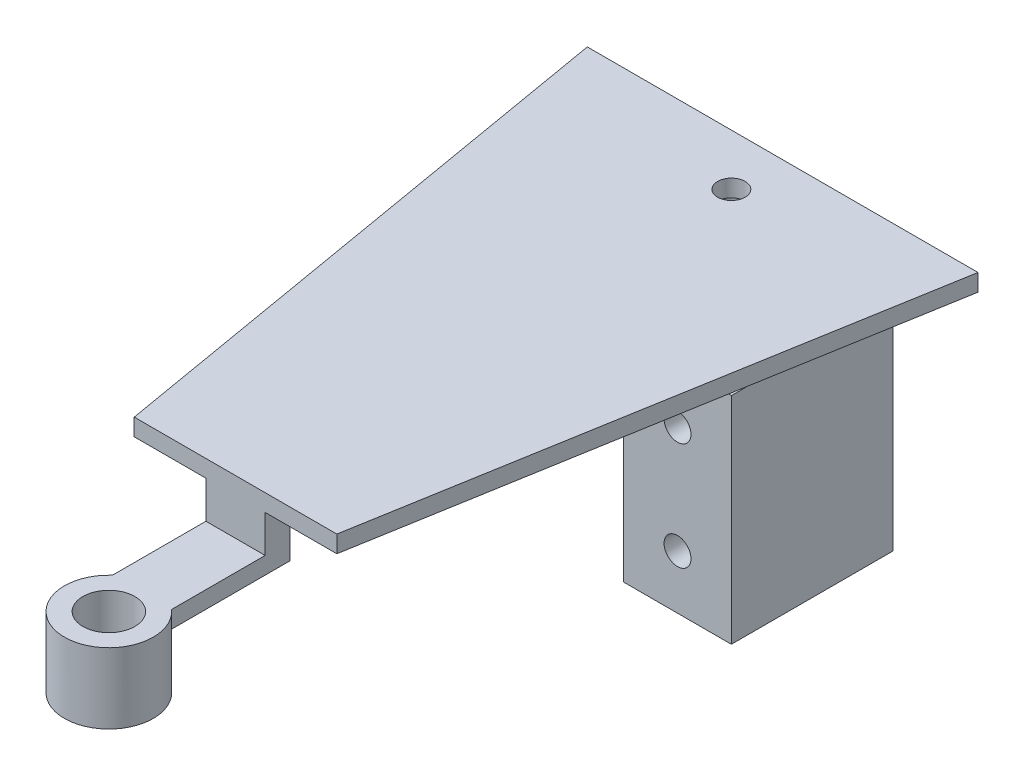
SolidWorks part; units mm, degrees
ref_plane "Front Plane" through (0, 0, 0) normal (0, 0, 1) x (1, 0, 0)
ref_plane "Top Plane" through (0, 0, 0) normal (0, 1, 0) x (1, 0, 0)
ref_plane "Right Plane" through (0, 0, 0) normal (1, 0, 0) x (0, 0, -1)
sketch "Sketch1" plane through (0, 0, 0) normal (0, 0, 1) x (1, 0, 0)
  line L0 (10, 40) -> (10, 0) construction
  line L1 (0, 0) -> (20, 0)
  line L2 (0, 0) -> (0, 40)
  line L3 (0, 40) -> (20, 40)
  line L4 (20, 0) -> (20, 40)
  circle A0 centre (10, 30) radius 2.5
  circle A1 centre (10, 10) radius 2.5
  dimension "D1" = 5
  dimension "D2" = 20
  dimension "D3" = 40
  dimension "D4" = 10
  dimension "D5" = 20
extrude "Boss-Extrude1" add sketch "Sketch1" against normal blind 30
sketch "Sketch3" plane through (0, 40, 0) normal (0, 1, 0) x (1, 0, 0)
  line L0 (10, 30) -> (10, 0) construction
  line L1 (20, 30) -> (0, 30) construction
  line L2 (20, 0) -> (0, 0) construction
  circle A1 centre (10, 10) radius 9.525
  dimension "D1" = 10
  dimension "D4" = 19.05
extrude "Boss-Extrude2" add sketch "Sketch3" along normal blind 20
ref_plane "Plane1" through (0, 60, 0) normal (0, 1, 0) x (1, 0, 0)
sketch "Sketch5" plane through (0, 60, 0) normal (0, 1, 0) x (1, 0, 0)
  circle A0 centre (10, 10) radius 3.175
  circle A1 centre (10, 10) radius 9.525 construction
  circle A2 centre (10, 10) radius 9.525 construction
  dimension "D1" = 6.35
extrude "Cut-Extrude1" cut sketch "Sketch5" against normal up to surface (20 mm away) up to face at (10, 40, -0.475)
sketch "Sketch4" plane through (0, 60, 0) normal (0, 1, 0) x (1, 0, 0)
  line L0 (46.2738, 19.525) -> (-26.2738, 19.525)
  line L5 (-26.2738, 19.525) -> (-8.8104, -82.075)
  line L6 (-8.8104, -82.075) -> (28.8104, -82.075)
  line L7 (10, 10) -> (10, -94.8535) construction
  line L8 (46.2738, 19.525) -> (28.8104, -82.075)
  circle A0 centre (10, -73.185) radius 4.826
  circle A1 centre (10, 10) radius 9.525
  circle A2 centre (10, 10) radius 9.525 construction
  point P11 (10, -82.075)
  dimension "D2" = 9.652
  dimension "D3" = 8.89
  dimension "D4" = 101.6
  dimension "D1" = 0
extrude "Boss-Extrude3" add sketch "Sketch4" along normal blind 3.175 separate body contours L8 L0 L5 L6 A0 | A0
ref_plane "Plane2" through (0, 40, 0) normal (0, 1, 0) x (1, 0, 0)
sketch "Sketch7" plane through (0, 40, 0) normal (0, 1, 0) x (1, 0, 0)
  line L0 (10, 0) -> (10, -123.4409) construction
  line L4 (0, 0) -> (20, 0)
  line L5 (20, 0) -> (20, 30)
  line L6 (20, 30) -> (0, 30)
  line L7 (0, 30) -> (0, 0)
  line L8 (0, 0) -> (20, 0) construction
  line L9 (20, 0) -> (20, 30) construction
  line L10 (20, 30) -> (0, 30) construction
  line L11 (0, 30) -> (0, 0) construction
  circle A0 centre (10, -105.6) radius 4.826
  circle A1 centre (10, -105.6) radius 8.255
  point P9 (10, -95.4885)
  dimension "D1" = 9.652
  dimension "D2" = 16.51
  dimension "D4" = 105.6
  dimension "D3" = 0
extrude "Boss-Extrude5" add sketch "Sketch7" along normal blind 13.081 separate body
sketch "Sketch8" plane through (0, 60, 0) normal (0, 1, 0) x (1, 0, 0)
  line L1 (34.0751, -86.8852) -> (-19.5618, -86.8852)
  line L2 (34.0751, -86.8852) -> (34.0751, -57.4898)
  line L3 (34.0751, -57.4898) -> (-19.5618, -57.4898)
  line L4 (-19.5618, -86.8852) -> (-19.5618, -57.4898)
sketch "Sketch9" plane through (0, 53.081, 0) normal (0, 1, 0) x (1, 0, 0)
  line L1 (4.5, -99.4441) -> (15.5, -99.4441)
  line L2 (4.5, -99.4441) -> (4.5, -77.4441)
  line L3 (4.5, -77.4441) -> (15.5, -77.4441)
  line L4 (15.5, -99.4441) -> (15.5, -77.4441)
  circle A0 centre (10, -105.6) radius 8.255 construction
  dimension "D1" = 11
  dimension "D2" = 22
extrude "Boss-Extrude6" add sketch "Sketch9" against normal blind 3.175
sketch "Sketch10" plane through (0, 53.081, 0) normal (0, 1, 0) x (1, 0, 0)
  line L10 (-8.8104, -82.075) -> (28.8104, -82.075) construction
  line L11 (4.5, -82.075) -> (15.5, -82.075)
  line L13 (15.5, -99.4441) -> (15.5, -77.4441)
  line L14 (15.5, -77.4441) -> (4.5, -77.4441)
  line L15 (4.5, -77.4441) -> (4.5, -99.4441)
  line L16 (15.5, -82.075) -> (15.5, -77.4441)
  line L17 (15.5, -77.4441) -> (4.5, -77.4441)
  line L18 (4.5, -77.4441) -> (4.5, -82.075)
  arc A1 (4.5, -99.4441) -> (15.5, -99.4441) centre (10, -105.6) ccw
  point P9 (4.5, -52.6441)
  point P10 (15.5, -52.6441)
  dimension "D1" = 0
extrude "Boss-Extrude7" add sketch "Sketch10" along normal up to surface (6.919 mm away) up to face at (10, 60, 31.275)
combine bodies "Combine1" operation type add bodies to combine 109 103
sketch "Sketch11" plane through (15.5, 0, 0) normal (1, 0, 0) x (0, 0, -1)
  line L0 (-82.075, 53.081) -> (-43.8157, 63.175)
  line L1 (19.525, 63.175) -> (-82.075, 63.175) construction
  line L2 (-43.8157, 63.175) -> (-42.978, 60)
  line L3 (30.4229, 60) -> (-30.4229, 60) construction
  line L4 (-42.978, 60) -> (-48.2303, 49.906)
  line L5 (-99.4441, 49.906) -> (-77.4441, 49.906) construction
  line L6 (-48.2303, 49.906) -> (-82.075, 53.081)
sketch "Sketch12" plane through (15.5, 0, 0) normal (1, 0, 0) x (0, 0, -1)
  line L0 (-82.075, 53.081) -> (-44.4636, 63.175)
  line L1 (19.525, 63.175) -> (-82.075, 63.175) construction
  line L6 (-82.075, 60) -> (19.525, 60)
  line L7 (-77.4441, 49.906) -> (-77.4441, 60)
  line L9 (-77.4441, 60) -> (-82.075, 60)
  line L10 (-82.075, 60) -> (-82.075, 53.081)
  line L11 (-82.075, 53.081) -> (-99.4441, 53.081)
  line L12 (-99.4441, 53.081) -> (-99.4441, 49.906)
  line L13 (-99.4441, 49.906) -> (-77.4441, 49.906)
  line L17 (-82.075, 60) -> (-82.075, 53.081)
  line L21 (19.525, 60) -> (19.525, 63.175)
  line L22 (19.525, 63.175) -> (-82.075, 63.175)
  line L23 (-82.075, 63.175) -> (-82.075, 60)
  line L26 (-44.4636, 63.175) -> (-82.075, 63.175)
  line L27 (-82.075, 63.175) -> (-82.075, 60)
  point P2 (-44.4016, 63.175)
  dimension "D1" = 0
  dimension "D2" = 0
sketch "Sketch13" plane through (0, 63.175, 0) normal (0, 1, 0) x (1, 0, 0)
  circle A0 centre (10, 10) radius 2.5527
  circle A1 centre (10, 10) radius 9.525
  circle A2 centre (10, 10) radius 9.525 construction
  point P5 (10.3122, 10)
  dimension "D2" = 5.1054
  dimension "D1" = 0
extrude "Cut-Extrude5" cut sketch "Sketch13" against normal blind 3.175
